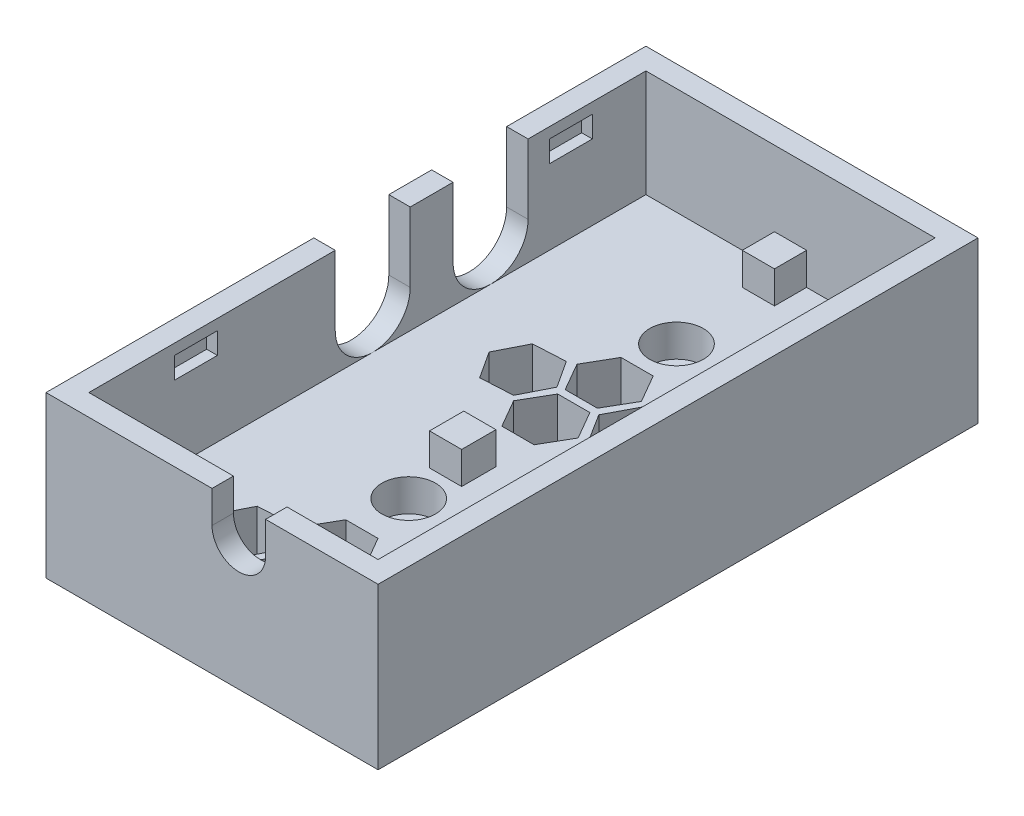
SolidWorks part; units mm, degrees
ref_plane "Plan de face" through (0, 0, 0) normal (0, 0, 1) x (1, 0, 0)
ref_plane "Plan de dessus" through (0, 0, 0) normal (0, 1, 0) x (1, 0, 0)
ref_plane "Plan de droite" through (0, 0, 0) normal (1, 0, 0) x (0, 0, -1)
sketch "Esquisse1" plane through (0, 0, 0) normal (0, 1, 0) x (1, 0, 0)
  line L1 (0, 0) -> (31, 0)
  line L2 (0, 0) -> (0, 56)
  line L3 (0, 56) -> (31, 56)
  line L4 (31, 0) -> (31, 56)
  dimension "D1" = 31
  dimension "D2" = 56
extrude "Boss.-Extru.1" add sketch "Esquisse1" along normal blind 5
sketch "Esquisse2" plane through (0, 5, 0) normal (0, 1, 0) x (1, 0, 0)
  line L0 (0, 0) -> (31, 0) construction
  line L1 (12.3982, 35.8349) -> (13.0045, 36.1849) construction
  line L2 (13.411, 34.2819) -> (11.7681, 36.8012)
  line L3 (18.3023, 35.3322) -> (17.7557, 35.7695) construction
  line L4 (15.5, 33.7672) -> (15.5, 34.4672) construction
  line L5 (15.5, 43.3565) -> (15.5, 55.8565) construction
  line L6 (15.5, 18.3565) -> (15.5, -4.1435) construction
  line L7 (13.2443, 32.4648) -> (12.7309, 32.9407) construction
  line L8 (11.7681, 36.8012) -> (8.7649, 36.638)
  line L9 (8.7649, 36.638) -> (7.4046, 33.9555)
  line L10 (7.4046, 33.9555) -> (9.0475, 31.4363)
  line L11 (9.0475, 31.4363) -> (12.0507, 31.5995)
  line L12 (12.0507, 31.5995) -> (13.411, 34.2819)
  line L13 (18.5076, 37.0719) -> (17.0038, 39.6766)
  line L14 (17.0038, 39.6766) -> (13.9962, 39.6766)
  line L15 (13.9962, 39.6766) -> (12.4924, 37.0719)
  line L16 (12.4924, 37.0719) -> (13.9962, 34.4672)
  line L17 (13.9962, 34.4672) -> (17.0038, 34.4672)
  line L18 (17.0038, 34.4672) -> (18.5076, 37.0719)
  line L19 (18.5076, 31.1625) -> (17.0038, 33.7672)
  line L20 (17.0038, 33.7672) -> (13.9962, 33.7672)
  line L21 (13.9962, 33.7672) -> (12.4924, 31.1625)
  line L22 (12.4924, 31.1625) -> (13.9962, 28.5578)
  line L23 (13.9962, 28.5578) -> (17.0038, 28.5578)
  line L24 (17.0038, 28.5578) -> (18.5076, 31.1625)
  line L25 (23.6124, 34.2359) -> (22.0083, 36.78)
  line L26 (22.0083, 36.78) -> (19.0029, 36.6628)
  line L27 (19.0029, 36.6628) -> (17.6017, 34.0015)
  line L28 (17.6017, 34.0015) -> (19.2059, 31.4574)
  line L29 (19.2059, 31.4574) -> (22.2112, 31.5746)
  line L30 (22.2112, 31.5746) -> (23.6124, 34.2359)
  line L31 (17.7557, 32.4648) -> (18.4038, 32.7295) construction
  line L32 (12.6799, 9.8643) -> (13.2861, 10.2143) construction
  line L33 (13.6927, 8.3113) -> (12.0498, 10.8306)
  line L34 (18.584, 9.3616) -> (18.0374, 9.799) construction
  line L35 (15.7817, 7.7966) -> (15.7817, 8.4966) construction
  line L36 (13.5259, 6.4943) -> (13.0126, 6.9701) construction
  line L37 (12.0498, 10.8306) -> (9.0466, 10.6674)
  line L38 (9.0466, 10.6674) -> (7.6863, 7.985)
  line L39 (7.6863, 7.985) -> (9.3292, 5.4657)
  line L40 (9.3292, 5.4657) -> (12.3324, 5.6289)
  line L41 (12.3324, 5.6289) -> (13.6927, 8.3113)
  line L42 (18.7893, 11.1013) -> (17.2855, 13.706)
  line L43 (17.2855, 13.706) -> (14.2779, 13.706)
  line L44 (14.2779, 13.706) -> (12.774, 11.1013)
  line L45 (12.774, 11.1013) -> (14.2779, 8.4966)
  line L46 (14.2779, 8.4966) -> (17.2855, 8.4966)
  line L47 (17.2855, 8.4966) -> (18.7893, 11.1013)
  line L48 (18.7893, 5.1919) -> (17.2855, 7.7966)
  line L49 (17.2855, 7.7966) -> (14.2779, 7.7966)
  line L50 (14.2779, 7.7966) -> (12.774, 5.1919)
  line L51 (12.774, 5.1919) -> (14.2779, 2.5872)
  line L52 (14.2779, 2.5872) -> (17.2855, 2.5872)
  line L53 (17.2855, 2.5872) -> (18.7893, 5.1919)
  line L54 (23.8941, 8.2653) -> (22.2899, 10.8094)
  line L55 (22.2899, 10.8094) -> (19.2846, 10.6923)
  line L56 (19.2846, 10.6923) -> (17.8834, 8.031)
  line L57 (17.8834, 8.031) -> (19.4875, 5.4868)
  line L58 (19.4875, 5.4868) -> (22.4929, 5.604)
  line L59 (22.4929, 5.604) -> (23.8941, 8.2653)
  line L60 (18.0374, 6.4943) -> (18.6855, 6.7589) construction
  circle A4 centre (15.5, 43.3565) radius 1.3
  circle A5 centre (15.5, 18.3565) radius 1.3
  circle A8 centre (10.4078, 34.1187) radius 2.6047 construction
  circle A9 centre (15.5, 37.0719) radius 2.6047 construction
  circle A10 centre (15.5, 31.1625) radius 2.6047 construction
  circle A11 centre (20.6071, 34.1187) radius 2.6047 construction
  circle A12 centre (10.6895, 8.1481) radius 2.6047 construction
  circle A13 centre (15.5, 11.1013) radius 2.8486 construction
  circle A14 centre (15.5, 5.1919) radius 2.8486 construction
  circle A15 centre (20.8887, 8.1481) radius 2.6047 construction
  point P3 (15.5, 0)
  point P51 (8.6282, 31.3722)
  point P52 (0, 0)
  point P53 (15.31, 36.3011)
  point P96 (0, 0)
  dimension "D6" = 2.6
  dimension "D1" = 0.7
  dimension "D2" = 0.7
  dimension "D7" = 25
  dimension "D8" = 12.5
  dimension "D9" = 22.5
extrude "Enlèv. mat.-Extru.1" cut sketch "Esquisse2" against normal through all
sketch "Esquisse4" plane through (0, 5, 0) normal (0, 1, 0) x (1, 0, 0)
  circle A0 centre (15.5, 43.3565) radius 2.5
  circle A1 centre (15.5, 18.3565) radius 2.5
  dimension "D1" = 5
extrude "Enlèv. mat.-Extru.2" cut sketch "Esquisse4" against normal blind 3
sketch "Esquisse5" plane through (0, 5, 0) normal (0, 1, 0) x (1, 0, 0)
  line L0 (31, 56) -> (0, 56) construction
  line L1 (14, 54) -> (17, 54)
  line L2 (14, 54) -> (14, 51)
  line L3 (14, 51) -> (17, 51)
  line L4 (17, 54) -> (17, 51)
  line L5 (0, 0) -> (31, 0) construction
  line L6 (14, 25) -> (17, 25)
  line L7 (14, 25) -> (14, 21.8003)
  line L8 (14, 21.8003) -> (17, 21.8003)
  line L9 (17, 25) -> (17, 21.8003)
  point P4 (15.5, 51)
  point P7 (15.5, 56)
  point P14 (15.5, 25)
  point P15 (15.5, 0)
  dimension "D1" = 25
  dimension "D2" = 3
  dimension "D3" = 3
  dimension "D4" = 2
  dimension "D5" = 3
extrude "Boss.-Extru.2" add sketch "Esquisse5" along normal blind 3
sketch "Esquisse6" plane through (0, 5, 0) normal (0, 1, 0) x (1, 0, 0)
  line L1 (0, 56) -> (31, 56)
  line L2 (0, 56) -> (0, 0)
  line L3 (0, 0) -> (31, 0)
  line L4 (31, 56) -> (31, 0)
  line L5 (2, 54) -> (29, 54)
  line L6 (2, 54) -> (2, 2)
  line L7 (2, 2) -> (29, 2)
  line L8 (29, 54) -> (29, 2)
  dimension "D1" = 2
  dimension "D2" = 2
  dimension "D3" = 2
  dimension "D4" = 2
extrude "Boss.-Extru.3" add sketch "Esquisse6" along normal blind 10
sketch "Esquisse8" plane through (0, 0, 0) normal (-1, 0, 0) x (0, 0, 1)
  line L0 (-43, 15) -> (-43, 8.5)
  line L1 (-56, 15) -> (0, 15) construction
  line L2 (-36, 8.5) -> (-36, 15)
  line L3 (-56, 15) -> (-56, 0) construction
  line L4 (-32, 15) -> (-32, 8.5)
  line L5 (-25, 8.5) -> (-25, 15)
  line L6 (-43, 15) -> (-36, 15)
  line L7 (-32, 15) -> (-25, 15)
  arc A0 (-43, 8.5) -> (-36, 8.5) centre (-39.5, 8.5) ccw
  arc A1 (-32, 8.5) -> (-25, 8.5) centre (-28.5, 8.5) ccw
  point P10 (0, 0)
  dimension "D3" = 6.5
  dimension "D1" = 13
  dimension "D2" = 7
  dimension "D4" = 2
extrude "Enlèv. mat.-Extru.3" cut sketch "Esquisse8" against normal blind 10
sketch "Esquisse9" plane through (0, 0, 0) normal (0, 0, 1) x (1, 0, 0)
  line L0 (15.5, 15) -> (15.5, 12)
  line L1 (0, 15) -> (31, 15) construction
  line L2 (20.5, 12) -> (20.5, 15)
  line L3 (20.5, 15) -> (15.5, 15)
  line L4 (31, 15) -> (31, 0) construction
  arc A0 (15.5, 12) -> (20.5, 12) centre (18, 12) ccw
  dimension "D1" = 5
  dimension "D2" = 3
  dimension "D3" = 13
extrude "Enlèv. mat.-Extru.4" cut sketch "Esquisse9" against normal blind 10
sketch "Esquisse10" plane through (29, 0, 0) normal (-1, 0, 0) x (0, 0, 1)
  line L0 (-56, 15) -> (-43, 15) construction
  line L1 (-45, 14) -> (-41, 14)
  line L2 (-45, 14) -> (-45, 12)
  line L3 (-45, 12) -> (-41, 12)
  line L4 (-41, 14) -> (-41, 12)
  line L5 (-56, 15) -> (-56, 0) construction
  line L6 (-16, 14) -> (-16, 12)
  line L7 (-16, 14) -> (-12, 14)
  line L8 (-12, 14) -> (-12, 12)
  line L9 (-16, 12) -> (-12, 12)
  dimension "D1" = 2
  dimension "D2" = 4
  dimension "D3" = 1
  dimension "D4" = 11
  dimension "D5" = 2
extrude "Enlèv. mat.-Extru.5" cut sketch "Esquisse10" against normal blind 1
sketch "Esquisse11" plane through (2, 0, 0) normal (1, 0, 0) x (0, 0, -1)
  line L0 (0, 15) -> (56, 15) construction
  line L1 (10, 14) -> (14, 14)
  line L2 (10, 14) -> (10, 12)
  line L3 (10, 12) -> (14, 12)
  line L4 (14, 14) -> (14, 12)
  line L5 (0, 15) -> (0, 0) construction
  line L6 (45, 14) -> (49, 14)
  line L7 (45, 14) -> (45, 12)
  line L8 (45, 12) -> (49, 12)
  line L9 (49, 14) -> (49, 12)
  line L10 (56, 15) -> (56, 0) construction
  dimension "D1" = 1
  dimension "D2" = 4
  dimension "D3" = 2
  dimension "D4" = 10
  dimension "D5" = 2
  dimension "D6" = 4
  dimension "D7" = 1
  dimension "D8" = 7
extrude "Enlèv. mat.-Extru.6" cut sketch "Esquisse11" against normal blind 1
